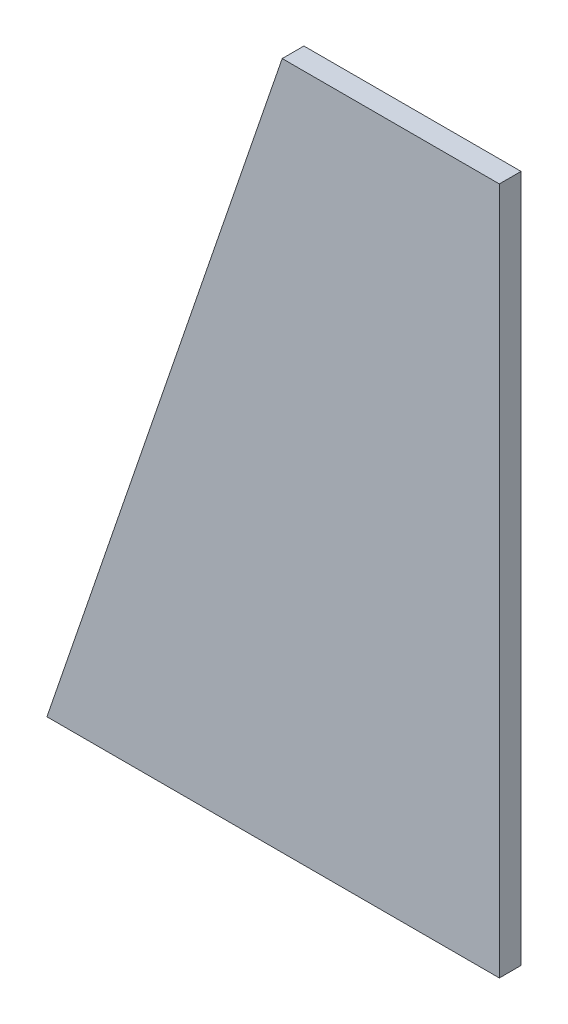
SolidWorks part; units mm, degrees
ref_plane "Front Plane" through (0, 0, 0) normal (0, 0, 1) x (1, 0, 0)
ref_plane "Top Plane" through (0, 0, 0) normal (0, 1, 0) x (1, 0, 0)
ref_plane "Right Plane" through (0, 0, 0) normal (1, 0, 0) x (0, 0, -1)
sketch "Sketch1" plane through (0, 0, 0) normal (0, 0, 1) x (1, 0, 0)
  line L0 (65, 190) -> (0, 0)
  line L1 (0, 0) -> (125, 0)
  line L3 (65, 190) -> (125, 190)
  line L4 (125, 0) -> (125, 190)
  line L5 (14.3684, 42) -> (125, 42)
  dimension "D1" = 190
  dimension "D2" = 125
  dimension "D3" = 60
  dimension "D4" = 42
extrude "Boss-Extrude1" add sketch "Sketch1" along normal mid plane 6 contours L0 L5 L4 L3 | L5 L0 L1 L4
ref_point "MAC_VTail" parameters "D1"=24
